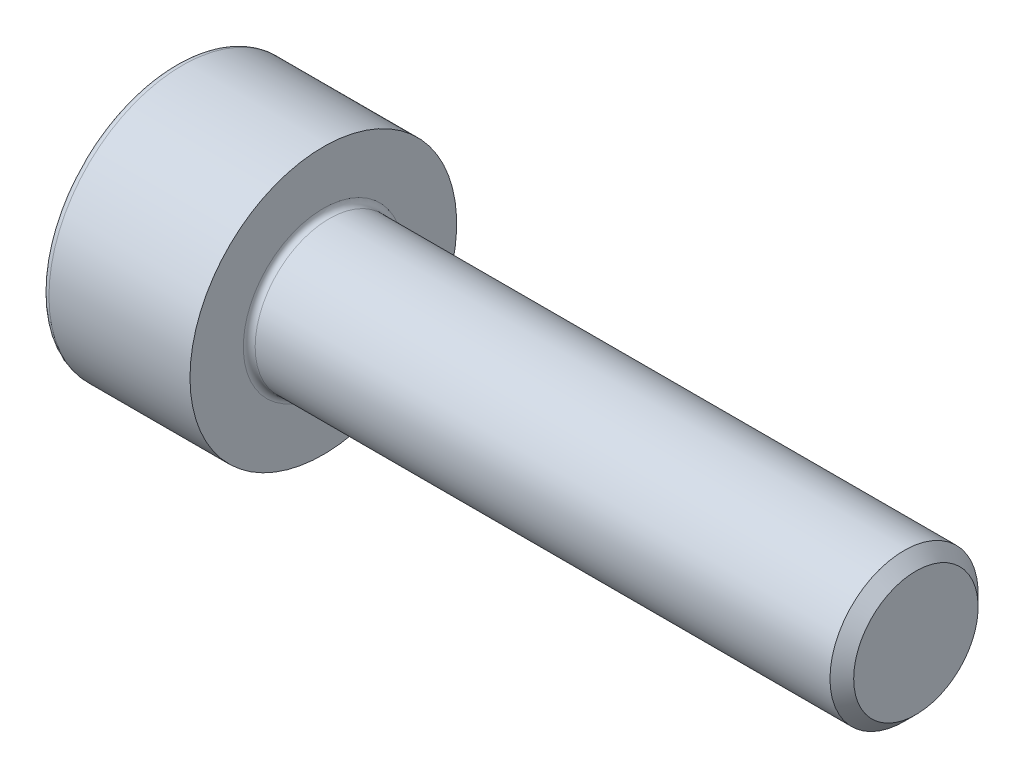
SolidWorks part; units mm, degrees
ref_plane "Front Plane" through (0, 0, 0) normal (0, 0, 1) x (1, 0, 0)
ref_plane "Top Plane" through (0, 0, 0) normal (0, 1, 0) x (1, 0, 0)
ref_plane "Right Plane" through (0, 0, 0) normal (1, 0, 0) x (0, 0, -1)
sketch "Sketch1" plane through (0, 0, 0) normal (0, 0, 1) x (1, 0, 0)
  line L0 (0, 0) -> (0, 2.25)
  line L1 (0, 2.25) -> (2.5, 2.25)
  line L2 (2.5, 2.25) -> (2.5, 0)
  line L3 (0, 0) -> (4.2799, 0) construction
  line L4 (2.5, 0) -> (12.5, 0)
  line L5 (12.5, 0) -> (12.5, 1.25)
  line L6 (12.5, 1.25) -> (2.5, 1.25)
  dimension "D1" = 10
revolve "Revolve1" add sketch "Sketch1" angle 360 about L3
fillet "Fillet1" radius 0.1 1 edges at (2.5, 0, 1.25)
fillet "Fillet2" radius 0.12 1 edges at (0, 0, 2.25)
chamfer "Chamfer1" distance 0.2 angle 45 1 edges at (12.5, 0, 1.25)
sketch "Sketch2" plane through (0, 0, 0) normal (-1, 0, 0) x (0, 0, 1)
  line L1 (0, 1.1547) -> (-1, 0.5774)
  line L2 (-1, 0.5774) -> (-1, -0.5774)
  line L3 (-1, -0.5774) -> (0, -1.1547)
  line L4 (0, -1.1547) -> (1, -0.5774)
  line L5 (1, -0.5774) -> (1, 0.5774)
  line L6 (1, 0.5774) -> (0, 1.1547)
  circle A0 centre (0, 0) radius 1 construction
extrude "Extrude1" cut sketch "Sketch2" against normal blind 1
